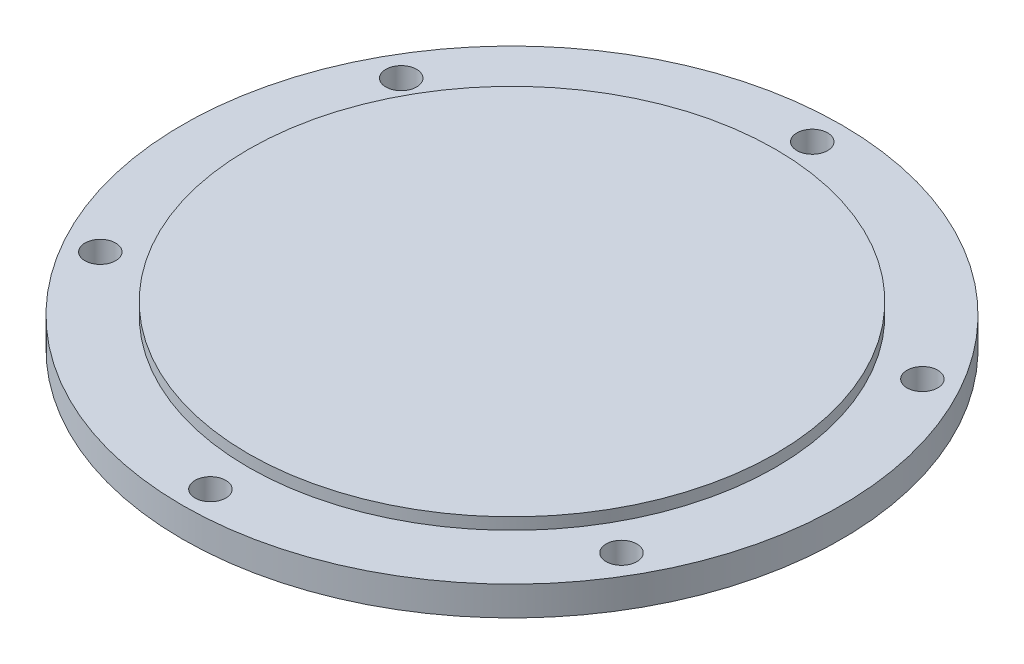
SolidWorks part; units mm, degrees
ref_plane "Alzado" through (0, 0, 0) normal (0, 0, 1) x (1, 0, 0)
ref_plane "Planta" through (0, 0, 0) normal (0, 1, 0) x (1, 0, 0)
ref_plane "Vista lateral" through (0, 0, 0) normal (1, 0, 0) x (0, 0, -1)
sketch "Croquis1" plane through (0, 0, 0) normal (0, 1, 0) x (1, 0, 0)
  circle A0 centre (0, 0) radius 112.5
  dimension "D1" = 225
extrude "Saliente-Extruir1" add sketch "Croquis1" along normal blind 10
sketch "Croquis2" plane through (0, 10, 0) normal (0, 1, 0) x (1, 0, 0)
  circle A0 centre (0, 0) radius 102.5
  dimension "D1" = 205
sketch "Croquis4" plane through (0, 10, 0) normal (0, 1, 0) x (1, 0, 0)
  line L0 (0, 0) -> (0, 135.6598)
hole_wizard "Taladro roscado M12x1.51" positions "Croquis3D2" profile "Croquis5" tap size "M12x1.5" standard "Ansi Metric"
sketch3d "Croquis3D2"
  line L0 (0, 10, 0) -> (0, 10, -135.6598) construction
  circle A0 centre (0, 10, 0) radius 102.5 construction
  point P0 (0, 10, -102.5)
  point P4 (0, 112.5, 0)
sketch "Croquis5" plane through (0, 10, -102.5) normal (1, 0, 0) x (0, 0, 1)
  line L0 (0, 0) -> (0, 34.6545)
  line L1 (0, 34.6545) -> (5.25, 31.5)
  line L2 (5.25, 31.5) -> (5.25, 0)
  line L5 (5.25, 0) -> (0, 0)
  line L10 (0, 34.6545) -> (-5.25, 31.5) construction
  line L11 (0, -6.35) -> (0, 107.95) construction
  dimension "Diámetro de perforador para roscar" = 10.5
  dimension "Profundidad de perforador para roscar" = 31.5
  dimension "Ángulo de perforador" = 118
pattern_circular "MatrizC1" count 6 over 360 about axis through (0, 0, 0.2237) along (0, 1, 0) of "Taladro roscado M12x1.51"
sketch "Croquis6" plane through (0, 10, 0) normal (0, 1, 0) x (1, 0, 0)
  circle A2 centre (0, 0) radius 90
  dimension "D1" = 180
extrude "Saliente-Extruir2" add sketch "Croquis6" along normal blind 4
